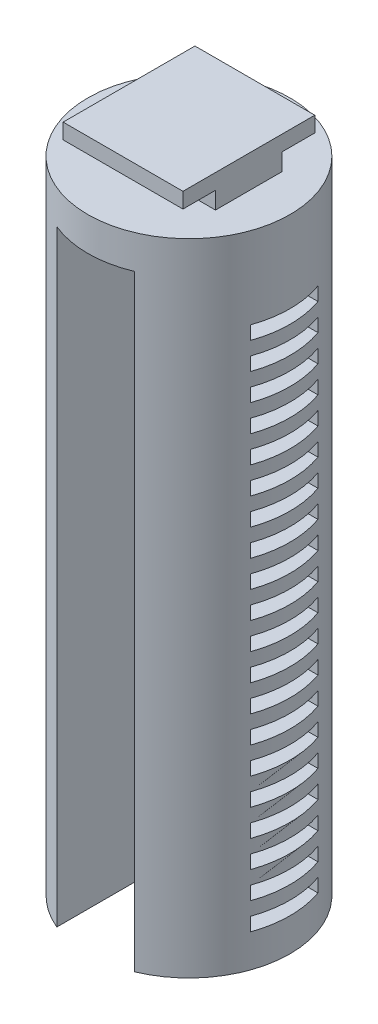
SolidWorks part; units mm, degrees
material "ABS"
ref_plane "Front Plane" through (0, 0, 0) normal (0, 0, 1) x (1, 0, 0)
ref_plane "Top Plane" through (0, 0, 0) normal (0, 1, 0) x (1, 0, 0)
ref_plane "Right Plane" through (0, 0, 0) normal (1, 0, 0) x (0, 0, -1)
sketch "Sketch1" plane through (0, 0, 0) normal (0, 1, 0) x (1, 0, 0)
  line L0 (-5.75, 13.8542) -> (-5.75, -13.8542)
  line L1 (5.75, 13.8542) -> (5.75, -13.8542)
  arc A0 (-5.75, 13.8542) -> (-5.75, -13.8542) centre (0, 0) ccw
  circle A1 centre (0, 0) radius 5 construction
  arc A2 (5.75, -13.8542) -> (5.75, 13.8542) centre (0, 0) ccw
  circle A3 centre (0, 0) radius 8
  circle A4 centre (-8, 0) radius 1.25
  circle A5 centre (8, 0) radius 1.25
  dimension "D1" = 30
  dimension "D4" = 10
  dimension "D5" = 16
  dimension "D6" = 2.5
  dimension "D7" = 2.5
  dimension "D2" = 5.75
  dimension "D3" = 5.75
extrude "Boss-Extrude1" add sketch "Sketch1" along normal blind 90 contours L0 A0 | A2 L1
sketch "Sketch2" plane through (0, 90, 0) normal (0, 1, 0) x (1, 0, 0)
  circle A0 centre (0, 0) radius 15
  arc A1 (5.75, -13.8542) -> (5.75, 13.8542) centre (0, 0) ccw construction
extrude "Boss-Extrude2" add sketch "Sketch2" along normal blind 5
ref_plane "Plane1" through (-15, 0, 0) normal (-1, 0, 0) x (0, 0, 1)
sketch "Sketch3" plane through (-15, 0, 0) normal (-1, 0, 0) x (0, 0, 1)
  line L0 (-13.8542, 0) -> (13.8542, 0) construction
  line L1 (-5, 4.9) -> (5, 4.9)
  line L2 (-5, 4.9) -> (-5, 6.9)
  line L3 (-5, 6.9) -> (5, 6.9)
  line L4 (5, 4.9) -> (5, 6.9)
  line L5 (0, 90) -> (0, 0) construction
  point P8 (0, 4.9)
  dimension "D1" = 10
  dimension "D2" = 2
  dimension "D3" = 4.9
sketch "Sketch4" plane through (0, 95, 0) normal (0, 1, 0) x (1, 0, 0)
  line L0 (-8.89, 4.953) -> (8.89, 4.953)
  line L1 (-8.89, 15.367) -> (8.89, 15.367)
  line L2 (-8.89, 15.367) -> (-8.89, -15.367)
  line L3 (-8.89, -15.367) -> (8.89, -15.367)
  line L4 (8.89, 15.367) -> (8.89, -15.367)
  line L5 (-8.89, 15.367) -> (8.89, -15.367) construction
  line L6 (-8.89, -15.367) -> (8.89, 15.367) construction
  line L7 (-8.89, -4.953) -> (8.89, -4.953)
  point P0 (0, 0)
  dimension "D1" = 30.734
  dimension "D2" = 17.78
  dimension "D3" = 10.414
  dimension "D4" = 10.414
extrude "Boss-Extrude3" add sketch "Sketch4" along normal blind 4.826 contours L2 L7 L4 L0
sketch "Sketch9" plane through (0, 0, -4.953) normal (0, 0, -1) x (-1, 0, 0)
  line L1 (-8.89, 99.826) -> (8.89, 99.826)
  line L2 (-8.89, 99.826) -> (-8.89, 97.54)
  line L3 (-8.89, 97.54) -> (8.89, 97.54)
  line L4 (8.89, 99.826) -> (8.89, 97.54)
  dimension "D1" = 2.286
extrude "Boss-Extrude9" add sketch "Sketch9" along normal blind 4.826
ref_plane "Plane2" through (0, 0, 0) normal (0, 0, -1) x (-1, 0, 0)
extrude "Cut-Extrude1" cut sketch "Sketch3" against normal blind 7
ref_plane "Plane4" through (0, 0, 0) normal (-1, 0, 0) x (0, 0, 1)
mirror "Mirror2" about plane through (0, 0, 0) normal (-1, 0, 0) of "Cut-Extrude1"
sketch "Sketch7" plane through (-15, 0, 0) normal (-1, 0, 0) x (0, 0, 1)
  line L0 (-8.89, 84.6368) -> (8.89, 84.6368)
  line L1 (8.89, 64.266) -> (-8.89, 64.266)
  line L2 (8.89, 64.266) -> (8.89, 95)
  line L3 (8.89, 95) -> (-8.89, 95)
  line L4 (-8.89, 64.266) -> (-8.89, 95)
  line L5 (8.89, 64.266) -> (-8.89, 95) construction
  line L6 (8.89, 95) -> (-8.89, 64.266) construction
  line L7 (-8.89, 74.6292) -> (8.89, 74.6292)
  line L9 (0, 90) -> (0, 0) construction
  line L10 (15, 95) -> (-15, 95) construction
  point P0 (0, 79.633)
  dimension "D1" = 17.78
  dimension "D2" = 30.734
  dimension "D3" = 10.3632
  dimension "D4" = 10.3632
  dimension "D5" = 10.3632
mirror "Mirror5" about plane through (0, 0, 0) normal (0, 0, -1) of "Boss-Extrude9"
pattern_linear "LPattern1" count 20 spacing 4 along (0, 1, 0) of "Cut-Extrude1", "Mirror2"
